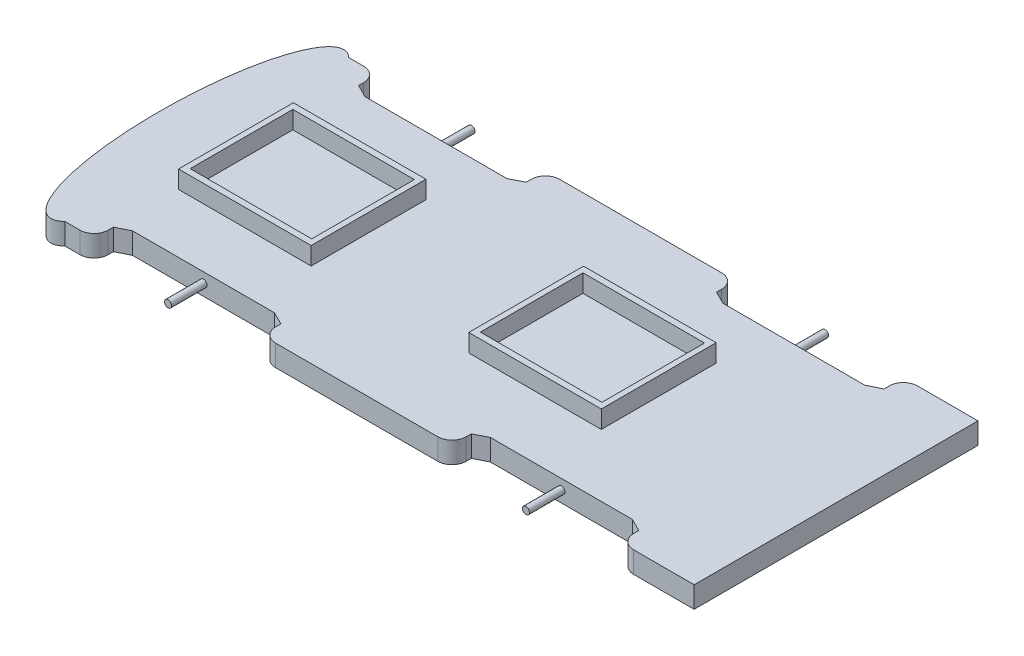
SolidWorks part; units mm, degrees
ref_plane "Front Plane" through (0, 0, 0) normal (0, 0, 1) x (1, 0, 0)
ref_plane "Top Plane" through (0, 0, 0) normal (0, 1, 0) x (1, 0, 0)
ref_plane "Right Plane" through (0, 0, 0) normal (1, 0, 0) x (0, 0, -1)
sketch "Sketch1" plane through (0, 0, 0) normal (0, 1, 0) x (1, 0, 0)
  line L0 (-87.7795, 50.8) -> (-87.7795, 43.8898)
  line L1 (-98.2146, 50.8) -> (127, 50.8)
  line L3 (-98.2146, -50.8) -> (127, -50.8)
  line L6 (127, 50.8) -> (127, -50.8)
  line L7 (-87.7795, 43.8898) -> (-83.2075, 41.6038)
  line L8 (-83.2075, 41.6038) -> (-32.4075, 41.6038)
  line L10 (-27.8355, 43.8898) -> (-32.4075, 41.6038)
  line L11 (-27.8355, 50.8) -> (-27.8355, 43.8898)
  line L13 (40.3376, 50.8) -> (40.3376, 43.8898)
  line L14 (40.3376, 43.8898) -> (44.9096, 41.6038)
  line L15 (95.7096, 41.6038) -> (44.9096, 41.6038)
  line L16 (100.2816, 43.8898) -> (95.7096, 41.6038)
  line L17 (100.2816, 50.8) -> (100.2816, 43.8898)
  line L19 (100.2816, -50.8) -> (100.2816, -43.8898)
  line L20 (100.2816, -43.8898) -> (95.7096, -41.6038)
  line L21 (95.7096, -41.6038) -> (44.9096, -41.6038)
  line L22 (40.3376, -43.8898) -> (44.9096, -41.6038)
  line L23 (40.3376, -50.8) -> (40.3376, -43.8898)
  line L24 (-27.8355, -50.8) -> (-27.8355, -43.8898)
  line L25 (-27.8355, -43.8898) -> (-32.4075, -41.6038)
  line L26 (-87.7795, -43.8898) -> (-83.2075, -41.6038)
  line L27 (-83.2075, -41.6038) -> (-32.4075, -41.6038)
  line L28 (-87.7795, -50.8) -> (-87.7795, -43.8898)
  ellipse E1 centre (-101.6, 0) end of major axis (-101.6, -52.3962) minor radius 13.8205 (-98.2146, -50.8) -> (-98.2146, 50.8) cw
  point P0 (0, 0)
extrude "Boss-Extrude1" add sketch "Sketch1" along normal blind 7.62
sketch "Sketch3" plane through (0, 0, 41.6038) normal (0, 0, 1) x (1, 0, 0)
  circle A0 centre (-57.8075, 4.0638) radius 1.27
  circle A1 centre (70.3096, 4.0638) radius 1.27
  point P0 (70.3096, 4.0638)
sketch "Sketch4" plane through (0, 0, -41.6038) normal (0, 0, -1) x (-1, 0, 0)
  circle A0 centre (-68.7402, 3.81) radius 1.27
  circle A1 centre (57.8075, 3.81) radius 1.27
  point P0 (57.8075, 3.81)
  point P4 (-68.7402, 3.81)
extrude "Boss-Extrude4" add sketch "Sketch3" along normal blind 12.7 contours A1 | A0
extrude "Boss-Extrude5" add sketch "Sketch4" along normal blind 12.7
sketch "Sketch5" plane through (0, 7.62, 0) normal (0, 1, 0) x (1, 0, 0)
  line L0 (16.7745, 19.639) -> (60.2938, 19.639)
  line L1 (-85.8182, 18.3698) -> (-42.2989, 18.3698)
  line L2 (-85.8182, 18.3698) -> (-85.8182, -18.3698)
  line L3 (-85.8182, -18.3698) -> (-42.2989, -18.3698)
  line L4 (-40.3376, -20.5452) -> (-87.7795, -20.5452)
  line L5 (-40.3376, -20.5452) -> (-40.3376, 20.5452)
  line L6 (-40.3376, 20.5452) -> (-87.7795, 20.5452)
  line L7 (-87.7795, -20.5452) -> (-87.7795, 20.5452)
  line L10 (-42.2989, 18.3698) -> (-42.2989, -18.3698)
  line L11 (-85.8182, 18.3698) -> (-42.2989, -18.3698) construction
  line L12 (-85.8182, -18.3698) -> (-42.2989, 18.3698) construction
  line L21 (16.7745, 19.639) -> (16.7745, -17.1006)
  line L22 (16.7745, -17.1006) -> (60.2938, -17.1006)
  line L23 (62.2551, -19.276) -> (14.8132, -19.276)
  line L24 (62.2551, -19.276) -> (62.2551, 21.8143)
  line L25 (62.2551, 21.8143) -> (14.8132, 21.8143)
  line L26 (14.8132, -19.276) -> (14.8132, 21.8143)
  line L27 (60.2938, 19.639) -> (60.2938, -17.1006)
  line L28 (16.7745, 19.639) -> (60.2938, -17.1006) construction
  line L29 (16.7745, -17.1006) -> (60.2938, 19.639) construction
  point P0 (-64.0585, 0)
  point P6 (-64.0585, 0)
  point P11 (38.5342, 1.2692)
  point P16 (38.5342, 1.2692)
extrude "Boss-Extrude7" add sketch "Sketch5" along normal blind 6.35
fillet "Fillet12" radius 5.08 8 edges at (-87.7795, 3.81, -50.8) (40.3376, 3.81, -50.8) (-27.8355, 3.81, -50.8) (100.2816, 3.81, -50.8) (100.2816, 3.81, 50.8) (40.3376, 3.81, 50.8) (-27.8355, 3.81, 50.8) (-87.7795, 3.81, 50.8)
